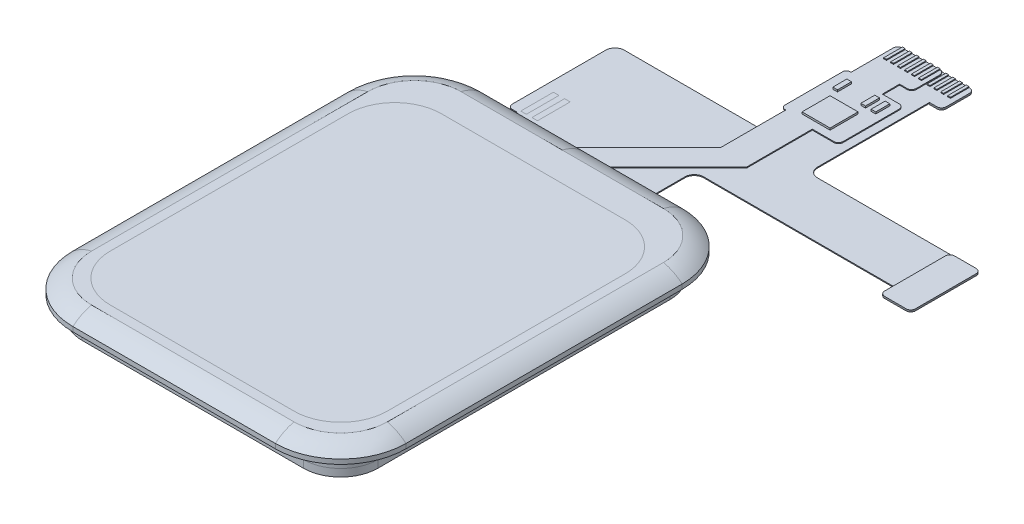
SolidWorks part; units mm, degrees
ref_plane "前视基准面" through (0, 0, 0) normal (0, 0, 1) x (1, 0, 0)
ref_plane "上视基准面" through (0, 0, 0) normal (0, 1, 0) x (1, 0, 0)
ref_plane "右视基准面" through (0, 0, 0) normal (1, 0, 0) x (0, 0, -1)
other "Configuration Table"
sketch "草图1" plane through (0, 0, 0) normal (0, 1, 0) x (1, 0, 0)
  line L1 (7, 0) -> (28.7, 0)
  line L2 (0, 7) -> (0, 36.6)
  line L3 (7, 43.6) -> (28.7, 43.6)
  line L4 (35.7, 7) -> (35.7, 36.6)
  arc A0 (0, 7) -> (7, 0) centre (7, 7) ccw
  arc A1 (28.7, 0) -> (35.7, 7) centre (28.7, 7) ccw
  arc A2 (35.7, 36.6) -> (28.7, 43.6) centre (28.7, 36.6) ccw
  arc A3 (0, 36.6) -> (7, 43.6) centre (7, 36.6) cw
  point P7 (0, 0)
  point P10 (35.7, 0)
  point P15 (0, 43.6)
  dimension "D3" = 7
  dimension "D1" = 35.7
  dimension "D2" = 43.6
extrude "凸台-拉伸1" add sketch "草图1" along normal blind 1.5
sketch "草图2" plane through (0, 1.5, 0) normal (0, 1, 0) x (1, 0, 0)
  line L4 (7, 0) -> (28.7, 0)
  line L5 (35.7, 7) -> (35.7, 36.6)
  line L6 (28.7, 43.6) -> (7, 43.6)
  line L7 (0, 36.6) -> (0, 7)
  line L8 (7, 0) -> (28.7, 0)
  line L9 (35.7, 7) -> (35.7, 36.6)
  line L10 (28.7, 43.6) -> (7, 43.6)
  line L11 (0, 36.6) -> (0, 7)
  arc A4 (0, 7) -> (7, 0) centre (7, 7) ccw
  arc A5 (28.7, 0) -> (35.7, 7) centre (28.7, 7) ccw
  arc A6 (35.7, 36.6) -> (28.7, 43.6) centre (28.7, 36.6) ccw
  arc A7 (7, 43.6) -> (0, 36.6) centre (7, 36.6) ccw
  arc A8 (0, 7) -> (7, 0) centre (7, 7) ccw
  arc A9 (28.7, 0) -> (35.7, 7) centre (28.7, 7) ccw
  arc A10 (35.7, 36.6) -> (28.7, 43.6) centre (28.7, 36.6) ccw
  arc A11 (7, 43.6) -> (0, 36.6) centre (7, 36.6) ccw
  dimension "D1" = 0
ref_plane "基准面1" through (17.85, 0, 0) normal (-1, 0, 0) x (0, 0, 1)
sketch "草图3" plane through (17.85, 0, 0) normal (-1, 0, 0) x (0, 0, 1)
  line L0 (-43.6, 1.5) -> (-43.6, 0.5)
  line L1 (-43.6, 1.5) -> (-43.6, 0) construction
  line L2 (-43.6, 1.5) -> (-41.6, 1.5)
  line L3 (-7, 1.5) -> (-36.6, 1.5) construction
  spline S0 degree 2 poles (-43.6, 0.5) (-42.7303, 1.2446) (-41.6, 1.5) knots 0 0 0 1 1 1
  dimension "D1" = 2
  dimension "D2" = 1
  dimension "D3" = 1.3607
  dimension "D4" = 0.7294
sweep "切除-扫描1" cut profiles "草图3" path "草图2"
sketch "草图5" plane through (0, 1.5, 0) normal (0, 1, 0) x (1, 0, 0)
  line L0 (7, 43.6) -> (0, 43.6) construction
  line L1 (0, 43.6) -> (0, 36.6) construction
  line L2 (0, 7) -> (0, 36.6) construction
  line L3 (0, 36.6) -> (2, 36.6) construction
  line L4 (0, 43.6) -> (3, 43.6) construction
  line L5 (3, 43.6) -> (3, 38.5) construction
  line L7 (8, 38.5) -> (27.7, 38.5)
  line L8 (3, 33.5) -> (3, 8)
  line L9 (8, 3) -> (27.7, 3)
  line L10 (32.7, 33.5) -> (32.7, 8)
  arc A0 (32.7, 33.5) -> (27.7, 38.5) centre (27.7, 33.5) ccw
  arc A1 (32.7, 8) -> (27.7, 3) centre (27.7, 8) cw
  arc A2 (8, 3) -> (3, 8) centre (8, 8) cw
  arc A3 (3, 33.5) -> (8, 38.5) centre (8, 33.5) cw
  point P15 (32.7, 38.5)
  point P20 (3, 3)
  dimension "D5" = 5
  dimension "D1" = 3
  dimension "D2" = 5.1
  dimension "D3" = 29.7
  dimension "D4" = 35.5
split line "分割线1"
sketch "草图6" plane through (0, 0, 0) normal (0, -1, 0) x (1, 0, 0)
  line L0 (7, 0) -> (0, 0) construction
  line L1 (0, 0) -> (2, 0) construction
  line L2 (2, 0) -> (2, -2) construction
  line L4 (6, -2) -> (29.7, -2)
  line L5 (2, -6) -> (2, -37.3)
  line L6 (6, -41.3) -> (29.7, -41.3)
  line L7 (33.7, -6) -> (33.7, -37.3)
  arc A0 (33.7, -37.3) -> (29.7, -41.3) centre (29.7, -37.3) cw
  arc A1 (6, -41.3) -> (2, -37.3) centre (6, -37.3) cw
  arc A2 (2, -6) -> (6, -2) centre (6, -6) cw
  arc A3 (33.7, -6) -> (29.7, -2) centre (29.7, -6) ccw
  point P13 (2, -41.3)
  point P19 (33.7, -2)
  dimension "D5" = 4
  dimension "D1" = 2
  dimension "D2" = 2
  dimension "D3" = 31.7
  dimension "D4" = 39.3
extrude "凸台-拉伸2" add sketch "草图6" along normal blind 0.1 separate body
sketch "草图7" plane through (0, -0.1, 0) normal (0, -1, 0) x (1, 0, 0)
  line L4 (33.7, -37.3) -> (33.7, -6)
  line L5 (29.7, -2) -> (6, -2)
  line L6 (2, -6) -> (2, -37.3)
  line L7 (6, -41.3) -> (29.7, -41.3)
  line L8 (33.7, -37.3) -> (33.7, -6)
  line L9 (29.7, -2) -> (6, -2)
  line L10 (2, -6) -> (2, -37.3)
  line L11 (6, -41.3) -> (29.7, -41.3)
  arc A4 (29.7, -41.3) -> (33.7, -37.3) centre (29.7, -37.3) ccw
  arc A5 (33.7, -6) -> (29.7, -2) centre (29.7, -6) ccw
  arc A6 (6, -2) -> (2, -6) centre (6, -6) ccw
  arc A7 (2, -37.3) -> (6, -41.3) centre (6, -37.3) ccw
  arc A8 (29.7, -41.3) -> (33.7, -37.3) centre (29.7, -37.3) ccw
  arc A9 (33.7, -6) -> (29.7, -2) centre (29.7, -6) ccw
  arc A10 (6, -2) -> (2, -6) centre (6, -6) ccw
  arc A11 (2, -37.3) -> (6, -41.3) centre (6, -37.3) ccw
  dimension "D1" = 0
extrude "凸台-拉伸3" add sketch "草图7" along normal blind 1.4 separate body
sketch "草图8" plane through (0, -1.5, 0) normal (0, -1, 0) x (1, 0, 0)
  line L4 (33.7, -37.3) -> (33.7, -6)
  line L5 (29.7, -2) -> (6, -2)
  line L6 (2, -6) -> (2, -37.3)
  line L7 (6, -41.3) -> (29.7, -41.3)
  line L8 (33.7, -37.3) -> (33.7, -6)
  line L9 (29.7, -2) -> (6, -2)
  line L10 (2, -6) -> (2, -37.3)
  line L11 (6, -41.3) -> (29.7, -41.3)
  arc A4 (29.7, -41.3) -> (33.7, -37.3) centre (29.7, -37.3) ccw
  arc A5 (33.7, -6) -> (29.7, -2) centre (29.7, -6) ccw
  arc A6 (6, -2) -> (2, -6) centre (6, -6) ccw
  arc A7 (2, -37.3) -> (6, -41.3) centre (6, -37.3) ccw
  arc A8 (29.7, -41.3) -> (33.7, -37.3) centre (29.7, -37.3) ccw
  arc A9 (33.7, -6) -> (29.7, -2) centre (29.7, -6) ccw
  arc A10 (6, -2) -> (2, -6) centre (6, -6) ccw
  arc A11 (2, -37.3) -> (6, -41.3) centre (6, -37.3) ccw
  dimension "D1" = 0
extrude "凸台-拉伸4" add sketch "草图8" along normal blind 0.8 separate body
sketch "草图9" plane through (0, -0.1, 0) normal (0, -1, 0) x (1, 0, 0)
  line L0 (33.7, -37.3) -> (33.7, -41.3) construction
  line L1 (33.7, -41.3) -> (20.2, -41.3) construction
  line L4 (27.7, -51.55) -> (27.7, -58.55)
  line L5 (27.7, -58.55) -> (30, -58.55)
  line L6 (30.5, -59.05) -> (30.5, -65.05)
  line L7 (30, -65.55) -> (28.2, -65.55)
  line L8 (28.2, -65.55) -> (28.2, -67.4)
  line L10 (24.5, -70.4) -> (24.5, -65.9)
  line L13 (24.5, -65.9) -> (24.4, -65.9)
  line L14 (24, -65.5) -> (24, -59.3)
  line L17 (28.2, -67.4) -> (29, -67.4)
  line L18 (29.5, -67.9) -> (29.5, -70.4)
  line L19 (29, -70.9) -> (25, -70.9)
  line L21 (24.5, -51.9) -> (24.5, -58.9)
  line L22 (24.5, -58.9) -> (24.4, -58.9)
  line L24 (6, -41.3) -> (29.7, -41.3) construction
  line L25 (19.2, -42.3) -> (19.2, -43.05)
  line L26 (19.2, -43.05) -> (27.7, -51.55)
  line L27 (24.5, -51.9) -> (15.9, -43.3)
  line L28 (15.9, -43.3) -> (15.9, -42.3)
  line L30 (14.9, -41.3) -> (20.2, -41.3)
  arc A0 (29.5, -70.4) -> (29, -70.9) centre (29, -70.4) cw
  arc A1 (29.5, -67.9) -> (29, -67.4) centre (29, -67.9) ccw
  arc A2 (30.5, -65.05) -> (30, -65.55) centre (30, -65.05) cw
  arc A3 (30.5, -59.05) -> (30, -58.55) centre (30, -59.05) ccw
  arc A4 (24.4, -65.9) -> (24, -65.5) centre (24.4, -65.5) cw
  arc A5 (24, -59.3) -> (24.4, -58.9) centre (24.4, -59.3) cw
  arc A6 (25, -70.9) -> (24.5, -70.4) centre (25, -70.4) cw
  arc A7 (29.7, -41.3) -> (33.7, -37.3) centre (29.7, -37.3) ccw construction
  arc A8 (15.9, -42.3) -> (14.9, -41.3) centre (14.9, -42.3) ccw
  arc A9 (20.2, -41.3) -> (19.2, -42.3) centre (20.2, -42.3) ccw
  point P21 (29.5, -70.9)
  point P26 (29.5, -67.4)
  point P29 (30.5, -65.55)
  point P32 (30.5, -58.55)
  point P35 (24, -65.9)
  point P38 (24, -58.9)
  point P41 (24.5, -70.9)
  point P50 (18.6209, -41.3)
  point P53 (19.2, -41.3)
  dimension "D19" = 0.5
  dimension "D20" = 0.4
  dimension "D21" = 0.5
  dimension "D17" = 1
  dimension "D18" = 1
  dimension "D3" = 4
  dimension "D4" = 7
  dimension "D5" = 7
  dimension "D6" = 2.8
  dimension "D7" = 2.3
  dimension "D8" = 1.85
  dimension "D9" = 3.5
  dimension "D10" = 5
  dimension "D11" = 1.3
  dimension "D12" = 5
  dimension "D13" = 0.5
  dimension "D14" = 7
  dimension "D15" = 0.5
  dimension "D16" = 7
  dimension "D22" = 8.5
  dimension "D23" = 8.5
  dimension "D24" = 8.6
  dimension "D25" = 5.3
  dimension "D26" = 1
  dimension "D27" = 0.75
  dimension "D28" = 13.5
  dimension "D29" = 1.5791
extrude "凸台-拉伸5" add sketch "草图9" along normal blind 0.1 separate body
ref_plane "基准面2" through (0, -0.4, 0) normal (0, -1, 0) x (-1, 0, 0)
sketch "草图11" plane through (0, -0.4, 0) normal (0, -1, 0) x (-1, 0, 0)
  line L0 (-2, 37.3) -> (-2, 41.3) construction
  line L1 (-2, 41.3) -> (-10, 41.3) construction
  line L2 (-6, 41.3) -> (-29.7, 41.3) construction
  line L3 (-10, 41.3) -> (-10, 44.6)
  line L4 (-10, 44.6) -> (-9.5, 44.6)
  line L5 (-9, 45.1) -> (-9, 55.1)
  line L6 (-10, 56.1) -> (-26.5, 56.1)
  line L7 (-27.5, 57.1) -> (-27.5, 70.6)
  line L8 (-28, 71.1) -> (-32, 71.1)
  line L9 (-32.5, 70.6) -> (-32.5, 68.1)
  line L10 (-32, 67.6) -> (-31.2, 67.6)
  line L11 (-31.2, 67.6) -> (-31.2, 55.6)
  line L12 (-32.2, 54.6) -> (-49.2, 54.6)
  line L13 (-49.7, 54.1) -> (-49.7, 47.6)
  line L14 (-49.2, 47.1) -> (-46.9, 47.1)
  line L15 (-46.4, 47.6) -> (-46.4, 48.6)
  line L16 (-46.4, 48.6) -> (-26, 48.6)
  line L17 (-25, 47.6) -> (-25, 41.3)
  line L18 (-25, 41.3) -> (-10, 41.3)
  arc A0 (-27.5, 70.6) -> (-28, 71.1) centre (-28, 70.6) ccw
  arc A1 (-32, 71.1) -> (-32.5, 70.6) centre (-32, 70.6) ccw
  arc A2 (-32.5, 68.1) -> (-32, 67.6) centre (-32, 68.1) ccw
  arc A3 (-9, 45.1) -> (-9.5, 44.6) centre (-9.5, 45.1) cw
  arc A4 (-49.2, 54.6) -> (-49.7, 54.1) centre (-49.2, 54.1) ccw
  arc A5 (-46.4, 47.6) -> (-46.9, 47.1) centre (-46.9, 47.6) cw
  arc A6 (-49.2, 47.1) -> (-49.7, 47.6) centre (-49.2, 47.6) cw
  arc A7 (-9, 55.1) -> (-10, 56.1) centre (-10, 55.1) ccw
  arc A8 (-26.5, 56.1) -> (-27.5, 57.1) centre (-26.5, 57.1) cw
  arc A9 (-31.2, 55.6) -> (-32.2, 54.6) centre (-32.2, 55.6) cw
  arc A10 (-25, 47.6) -> (-26, 48.6) centre (-26, 47.6) ccw
  point P3 (0, 0)
  point P24 (-27.5, 71.1)
  point P27 (-32.5, 71.1)
  point P30 (-32.5, 67.6)
  point P33 (-9, 44.6)
  point P36 (-49.7, 54.6)
  point P39 (-46.4, 47.1)
  point P42 (-49.7, 47.1)
  point P45 (-9, 56.1)
  point P48 (-27.5, 56.1)
  point P51 (-31.2, 54.6)
  point P54 (-25, 48.6)
  dimension "D17" = 0.5
  dimension "D18" = 1
  dimension "D1" = 4
  dimension "D2" = 8
  dimension "D3" = 3.3
  dimension "D4" = 1
  dimension "D5" = 11.5
  dimension "D6" = 18.5
  dimension "D7" = 15
  dimension "D8" = 5
  dimension "D9" = 3.5
  dimension "D10" = 1.3
  dimension "D11" = 13
  dimension "D12" = 18.5
  dimension "D13" = 7.5
  dimension "D14" = 3.3
  dimension "D15" = 21.4
  dimension "D16" = 7.3
extrude "凸台-拉伸6" add sketch "草图11" along normal blind 0.1 separate body contours L17 L18 L3 L4 L5 L6 L7 L8 L9 L10 L11 L12 L13 L14 L15 L16
sketch "草图13" plane through (0, -0.4, 0) normal (0, 1, 0) x (1, 0, 0)
  line L0 (46.4, 48.6) -> (46.4, 54.1)
  line L1 (32.2, 54.6) -> (49.2, 54.6) construction
  line L2 (46.4, 47.6) -> (46.4, 48.6) construction
  line L3 (49.2, 47.1) -> (46.9, 47.1) construction
  line L4 (49.7, 54.1) -> (49.7, 47.6) construction
  line L5 (46.4, 47.6) -> (46.4, 48.6)
  line L6 (49.2, 47.1) -> (46.9, 47.1)
  line L7 (49.7, 54.1) -> (49.7, 47.6)
  line L8 (46.9, 54.6) -> (49.2, 54.6)
  arc A0 (46.4, 47.6) -> (46.9, 47.1) centre (46.9, 47.6) ccw construction
  arc A1 (49.2, 47.1) -> (49.7, 47.6) centre (49.2, 47.6) ccw construction
  arc A2 (49.7, 54.1) -> (49.2, 54.6) centre (49.2, 54.1) ccw construction
  arc A3 (46.4, 47.6) -> (46.9, 47.1) centre (46.9, 47.6) ccw
  arc A4 (49.2, 47.1) -> (49.7, 47.6) centre (49.2, 47.6) ccw
  arc A5 (49.7, 54.1) -> (49.2, 54.6) centre (49.2, 54.1) ccw
  arc A6 (46.9, 54.6) -> (46.4, 54.1) centre (46.9, 54.1) ccw
  dimension "D1" = 0.5
extrude "凸台-拉伸7" add sketch "草图13" along normal blind 0.1 separate body
sketch "草图14" plane through (0, -0.5, 0) normal (0, -1, 0) x (1, 0, 0)
  line L0 (48.05, -47.1) -> (48.05, -54.6)
  line L1 (49.2, -47.1) -> (46.9, -47.1) construction
  line L2 (32.2, -54.6) -> (49.2, -54.6) construction
  line L4 (47.05, -48.1) -> (49.05, -48.1)
  line L5 (47.05, -48.1) -> (47.05, -53.6)
  line L6 (47.05, -53.6) -> (49.05, -53.6)
  line L7 (49.05, -48.1) -> (49.05, -53.6)
  line L8 (47.05, -48.1) -> (49.05, -53.6) construction
  line L9 (47.05, -53.6) -> (49.05, -48.1) construction
  line L10 (46.8, -48.4) -> (49.3, -48.4)
  line L11 (46.8, -48.4) -> (46.8, -53.3)
  line L12 (46.8, -53.3) -> (49.3, -53.3)
  line L13 (49.3, -48.4) -> (49.3, -53.3)
  line L14 (46.8, -48.4) -> (49.3, -53.3) construction
  line L15 (46.8, -53.3) -> (49.3, -48.4) construction
  point P6 (48.05, -50.85)
  point P11 (48.05, -50.85)
  dimension "D1" = 5.5
  dimension "D2" = 2
  dimension "D3" = 2.5
  dimension "D4" = 4.9
extrude "凸台-拉伸8" add sketch "草图14" along normal blind 0.3 separate body contours L11 L12 L5 L10 | L5 L12 L0 L10 | L0 L12 L7 L10 | L12 L5 L6 L0 | L12 L0 L6 L7
sketch "草图15" plane through (0, -0.8, 0) normal (0, -1, 0) x (1, 0, 0)
  line L0 (48.05, -48.1) -> (48.05, -53.6)
  line L1 (47.05, -48.1) -> (49.05, -48.1) construction
  line L2 (47.05, -53.6) -> (49.05, -53.6) construction
  line L4 (47.55, -48.95) -> (48.55, -48.95)
  line L5 (47.55, -48.95) -> (47.55, -52.75)
  line L6 (47.55, -52.75) -> (48.55, -52.75)
  line L7 (48.55, -48.95) -> (48.55, -52.75)
  line L8 (47.55, -48.95) -> (48.55, -52.75) construction
  line L9 (47.55, -52.75) -> (48.55, -48.95) construction
  point P6 (48.05, -50.85)
  dimension "D1" = 1
  dimension "D2" = 3.8
extrude "切除-拉伸1" cut sketch "草图15" against normal blind 0.2 contours L5 L6 L0 L4 | L7 L4 L0 L6
sketch "草图16" plane through (0, -0.1, 0) normal (0, 1, 0) x (1, 0, 0)
  line L0 (24, 60.9) -> (27.25, 60.9) construction
  line L5 (25.75, 62.4) -> (28.75, 62.4)
  line L6 (25.75, 62.4) -> (25.75, 59.4)
  line L7 (25.75, 59.4) -> (28.75, 59.4)
  line L8 (28.75, 62.4) -> (28.75, 59.4)
  line L9 (25.75, 62.4) -> (28.75, 59.4) construction
  line L10 (25.75, 59.4) -> (28.75, 62.4) construction
  line L11 (24, 59.3) -> (24, 65.5) construction
  line L12 (24, 62.4) -> (24, 60.9) construction
  line L13 (29.7, 63.35) -> (30.5, 63.35) construction
  line L14 (29.7, 63.35) -> (29.2, 63.35)
  line L15 (29.7, 63.35) -> (29.7, 64.85)
  line L16 (29.7, 64.85) -> (29.2, 64.85)
  line L17 (29.2, 63.35) -> (29.2, 64.85)
  line L18 (28.6, 63.35) -> (28.1, 63.35)
  line L19 (28.6, 63.35) -> (28.6, 64.85)
  line L20 (28.6, 64.85) -> (28.1, 64.85)
  line L21 (28.1, 63.35) -> (28.1, 64.85)
  line L22 (25.6, 63.35) -> (25.1, 63.35)
  line L23 (25.6, 63.35) -> (25.6, 64.85)
  line L24 (25.6, 64.85) -> (25.1, 64.85)
  line L25 (25.1, 63.35) -> (25.1, 64.85)
  line L26 (30.5, 65.05) -> (30.5, 59.05) construction
  line L27 (28.6, 63.35) -> (29.2, 63.35) construction
  line L28 (30.5, 63.35) -> (30.5, 62.05) construction
  line L29 (28.1, 63.35) -> (25.6, 63.35) construction
  point P0 (27.25, 60.9)
  dimension "D1" = 3
  dimension "D2" = 3
  dimension "D3" = 1.5
  dimension "D4" = 3.25
  dimension "D5" = 1.5
  dimension "D6" = 0.5
  dimension "D7" = 0.5
  dimension "D8" = 1.5
  dimension "D9" = 1.5
  dimension "D10" = 0.5
  dimension "D11" = 1.3
  dimension "D12" = 0.8
  dimension "D13" = 0.6
  dimension "D14" = 2.5
extrude "凸台-拉伸9" add sketch "草图16" along normal blind 0.2 separate body
sketch "草图17" plane through (0, -0.1, 0) normal (0, 1, 0) x (1, 0, 0)
  line L0 (25.75, 68.9) -> (26.05, 68.9)
  line L1 (25, 70.9) -> (25.3, 70.9)
  line L2 (25, 70.9) -> (25, 68.9)
  line L3 (25, 68.9) -> (25.3, 68.9)
  line L4 (25.3, 70.9) -> (25.3, 68.9)
  line L5 (25.75, 70.9) -> (25.75, 68.9)
  line L6 (26.05, 70.9) -> (26.05, 68.9)
  line L7 (25.75, 70.9) -> (26.05, 70.9)
  line L8 (26.5, 68.9) -> (26.8, 68.9)
  line L9 (26.5, 70.9) -> (26.5, 68.9)
  line L10 (26.8, 70.9) -> (26.8, 68.9)
  line L11 (26.5, 70.9) -> (26.8, 70.9)
  line L12 (27.25, 68.9) -> (27.55, 68.9)
  line L13 (27.25, 70.9) -> (27.25, 68.9)
  line L14 (27.55, 70.9) -> (27.55, 68.9)
  line L15 (27.25, 70.9) -> (27.55, 70.9)
  line L16 (28, 68.9) -> (28.3, 68.9)
  line L17 (28, 70.9) -> (28, 68.9)
  line L18 (28.3, 70.9) -> (28.3, 68.9)
  line L19 (28, 70.9) -> (28.3, 70.9)
  line L20 (28.75, 68.9) -> (29.05, 68.9)
  line L21 (28.75, 70.9) -> (28.75, 68.9)
  line L22 (29.05, 70.9) -> (29.05, 68.9)
  line L23 (28.75, 70.9) -> (29.05, 70.9)
  dimension "D1" = 0.3
  dimension "D2" = 2
  dimension "D4" = 0.45
  dimension "D3" = 6
extrude "凸台-拉伸10" add sketch "草图17" along normal blind 0.1 and the other way blind 0.2 separate body
sketch "草图20" plane through (0, -0.4, 0) normal (0, 1, 0) x (1, 0, 0)
  line L0 (28.73, 69.1) -> (29.03, 69.1)
  line L1 (28, 71.1) -> (28.3, 71.1)
  line L2 (28, 71.1) -> (28, 69.1)
  line L3 (28, 69.1) -> (28.3, 69.1)
  line L4 (28.3, 71.1) -> (28.3, 69.1)
  line L5 (28.73, 71.1) -> (28.73, 69.1)
  line L6 (29.03, 71.1) -> (29.03, 69.1)
  line L7 (28.73, 71.1) -> (29.03, 71.1)
  line L8 (29.46, 69.1) -> (29.76, 69.1)
  line L9 (29.46, 71.1) -> (29.46, 69.1)
  line L10 (29.76, 71.1) -> (29.76, 69.1)
  line L11 (29.46, 71.1) -> (29.76, 71.1)
  line L12 (30.19, 69.1) -> (30.49, 69.1)
  line L13 (30.19, 71.1) -> (30.19, 69.1)
  line L14 (30.49, 71.1) -> (30.49, 69.1)
  line L15 (30.19, 71.1) -> (30.49, 71.1)
  line L16 (30.92, 69.1) -> (31.22, 69.1)
  line L17 (30.92, 71.1) -> (30.92, 69.1)
  line L18 (31.22, 71.1) -> (31.22, 69.1)
  line L19 (30.92, 71.1) -> (31.22, 71.1)
  line L20 (31.65, 69.1) -> (31.95, 69.1)
  line L21 (31.65, 71.1) -> (31.65, 69.1)
  line L22 (31.95, 71.1) -> (31.95, 69.1)
  line L23 (31.65, 71.1) -> (31.95, 71.1)
  dimension "D1" = 0.3
  dimension "D2" = 2
  dimension "D4" = 0.43
  dimension "D3" = 6
extrude "凸台-拉伸11" add sketch "草图20" along normal blind 0.1 separate body
sketch "草图21" plane through (0, -0.5, 0) normal (0, -1, 0) x (1, 0, 0)
  line L0 (10, -41.3) -> (12, -41.3) construction
  line L1 (6, -41.3) -> (29.7, -41.3) construction
  line L2 (10, -41.3) -> (19.27, -41.3) construction
  line L3 (12, -41.3) -> (12.6, -41.3)
  line L4 (12, -41.3) -> (12, -44.3)
  line L5 (12, -44.3) -> (12.6, -44.3)
  line L6 (12.6, -41.3) -> (12.6, -44.3)
  line L7 (25, -41.3) -> (10, -41.3) construction
  line L9 (19.27, -41.3) -> (20.27, -41.3)
  line L10 (19.27, -41.3) -> (19.27, -44.3)
  line L11 (19.27, -44.3) -> (20.27, -44.3)
  line L12 (20.27, -41.3) -> (20.27, -44.3)
  dimension "D1" = 2
  dimension "D2" = 9.27
  dimension "D3" = 0.6
  dimension "D4" = 3
  dimension "D5" = 1
  dimension "D6" = 3
extrude "切除-拉伸2" cut sketch "草图21" against normal blind 0.1
sketch "草图22" plane through (0, -0.4, 0) normal (0, 1, 0) x (1, 0, 0)
  line L0 (10.7, 44.9) -> (11.3, 44.9) construction
  line L1 (10.7, 44.9) -> (10.1, 44.9)
  line L2 (10.7, 44.9) -> (10.7, 48.4)
  line L3 (10.7, 48.4) -> (10.1, 48.4)
  line L4 (10.1, 44.9) -> (10.1, 48.4)
  line L5 (11.9, 44.9) -> (11.3, 44.9)
  line L6 (11.9, 44.9) -> (11.9, 48.4)
  line L7 (11.9, 48.4) -> (11.3, 48.4)
  line L8 (11.3, 44.9) -> (11.3, 48.4)
  line L9 (12, 41.3) -> (10, 41.3) construction
  line L10 (12, 41.3) -> (10, 41.3) construction
  line L11 (11, 44.9) -> (11, 41.3) construction
  dimension "D1" = 3.5
  dimension "D2" = 3.5
  dimension "D3" = 0.6
  dimension "D4" = 0.6
  dimension "D5" = 0.6
  dimension "D6" = 3.6
split line "分割线2"
sketch "草图23" plane through (0, -0.5, 0) normal (0, -1, 0) x (1, 0, 0)
  line L0 (31.2, -67.6) -> (28, -67.6)
  line L1 (27.5, -57.1) -> (27.5, -70.6) construction
  line L2 (28, -71.1) -> (32, -71.1) construction
  line L3 (32.5, -70.6) -> (32.5, -68.1) construction
  line L4 (32, -67.6) -> (31.2, -67.6) construction
  line L5 (27.5, -68.1) -> (27.5, -70.6)
  line L6 (28, -71.1) -> (32, -71.1)
  line L7 (32.5, -70.6) -> (32.5, -68.1)
  line L8 (32, -67.6) -> (31.2, -67.6)
  arc A0 (27.5, -70.6) -> (28, -71.1) centre (28, -70.6) ccw construction
  arc A1 (32, -71.1) -> (32.5, -70.6) centre (32, -70.6) ccw construction
  arc A2 (32.5, -68.1) -> (32, -67.6) centre (32, -68.1) ccw construction
  arc A3 (27.5, -70.6) -> (28, -71.1) centre (28, -70.6) ccw
  arc A4 (32, -71.1) -> (32.5, -70.6) centre (32, -70.6) ccw
  arc A5 (32.5, -68.1) -> (32, -67.6) centre (32, -68.1) ccw
  arc A6 (27.5, -68.1) -> (28, -67.6) centre (28, -68.1) cw
  point P11 (27.5, -67.6)
  dimension "D1" = 0.5
extrude "凸台-拉伸12" add sketch "草图23" along normal blind 0.1 separate body
